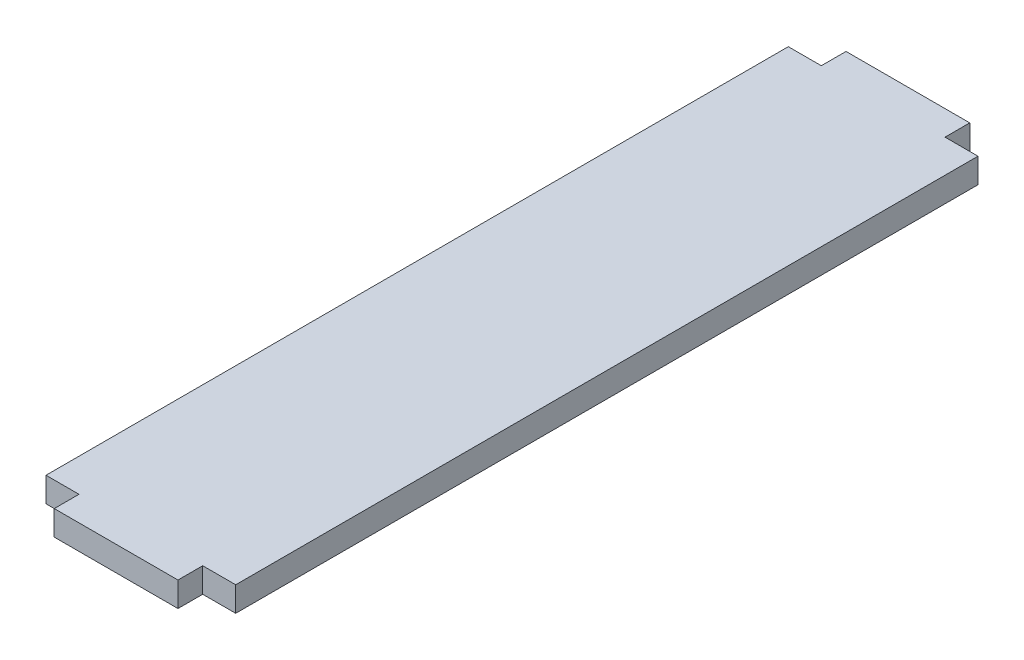
SolidWorks part; units mm, degrees
material "AISI 304"
ref_plane "Front Plane" through (0, 0, 0) normal (0, 0, 1) x (1, 0, 0)
ref_plane "Top Plane" through (0, 0, 0) normal (0, 1, 0) x (1, 0, 0)
ref_plane "Right Plane" through (0, 0, 0) normal (1, 0, 0) x (0, 0, -1)
sketch "Sketch1" plane through (0, 0, 0) normal (0, 1, 0) x (1, 0, 0)
  line L0 (3.75, 22.5) -> (5.75, 22.5)
  line L1 (-5.75, -22.5) -> (-3.75, -22.5)
  line L2 (-5.75, -22.5) -> (-5.75, 22.5)
  line L3 (-5.75, 22.5) -> (-3.75, 22.5)
  line L4 (5.75, -22.5) -> (5.75, 22.5)
  line L5 (-5.75, -22.5) -> (5.75, 22.5) construction
  line L6 (-5.75, 22.5) -> (5.75, -22.5) construction
  line L8 (-3.75, 22.5) -> (-3.75, 24)
  line L9 (-3.75, 24) -> (3.75, 24)
  line L10 (3.75, 22.5) -> (3.75, 24)
  line L12 (-3.75, -22.5) -> (-3.75, -24)
  line L13 (-3.75, -24) -> (3.75, -24)
  line L14 (3.75, -22.5) -> (3.75, -24)
  line L15 (3.75, -22.5) -> (5.75, -22.5)
  point P0 (0, 0)
  dimension "D1" = 7.5
  dimension "D2" = 2
  dimension "D3" = 2
  dimension "D4" = 45
  dimension "D5" = 2
  dimension "D6" = 2
  dimension "D7" = 1.5
  dimension "D8" = 1.5
extrude "Boss-Extrude1" add sketch "Sketch1" along normal blind 1.5
